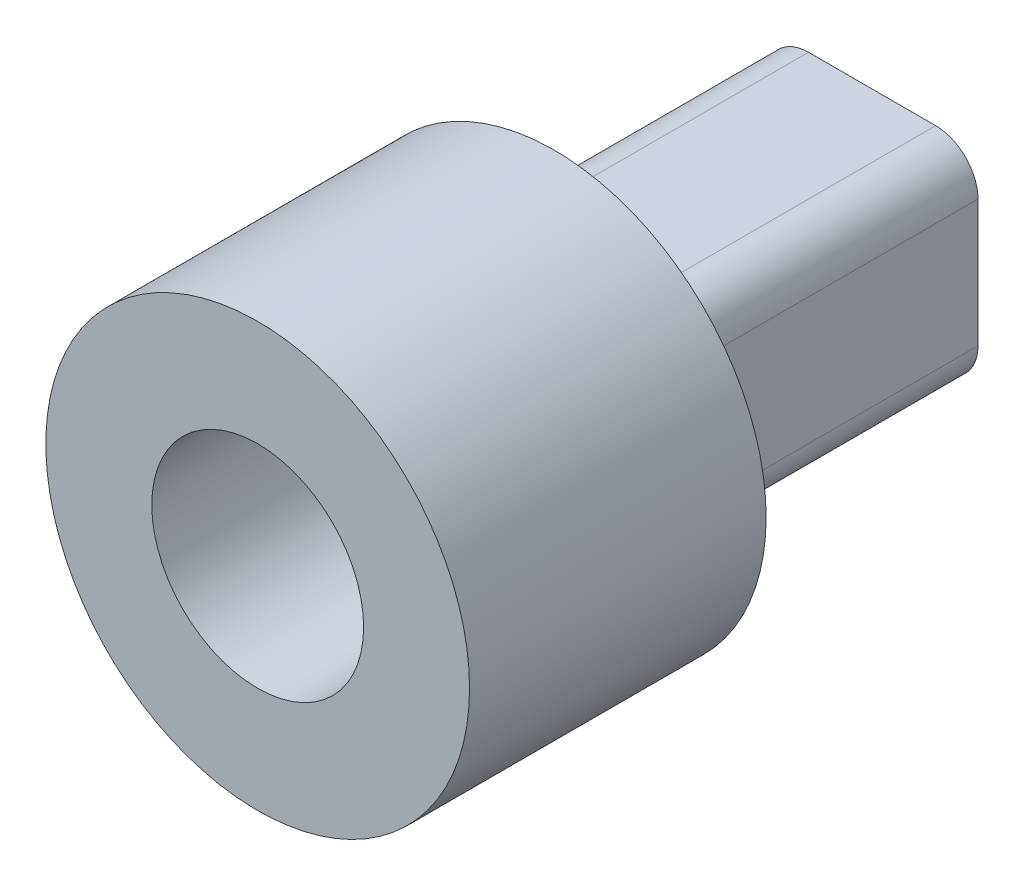
SolidWorks part; units mm, degrees
ref_plane "Front Plane" through (0, 0, 0) normal (0, 0, 1) x (1, 0, 0)
ref_plane "Top Plane" through (0, 0, 0) normal (0, 1, 0) x (1, 0, 0)
ref_plane "Right Plane" through (0, 0, 0) normal (1, 0, 0) x (0, 0, -1)
sketch "Sketch1" plane through (0, 0, 0) normal (0, 0, 1) x (1, 0, 0)
  line L1 (-1.5, -2.5) -> (1.5, -2.5)
  line L2 (-2.5, -1.5) -> (-2.5, 1.5)
  line L3 (-1.5, 2.5) -> (1.5, 2.5)
  line L4 (2.5, -1.5) -> (2.5, 1.5)
  line L5 (-2.5, -2.5) -> (2.5, 2.5) construction
  line L6 (-2.5, 2.5) -> (2.5, -2.5) construction
  arc A0 (1.5, 2.5) -> (2.5, 1.5) centre (1.5, 1.5) cw
  arc A1 (1.5, -2.5) -> (2.5, -1.5) centre (1.5, -1.5) ccw
  arc A2 (-1.5, -2.5) -> (-2.5, -1.5) centre (-1.5, -1.5) cw
  arc A3 (-2.5, 1.5) -> (-1.5, 2.5) centre (-1.5, 1.5) cw
  point P0 (0, 0)
  dimension "D3" = 1
  dimension "D1" = 5
  dimension "D2" = 5
extrude "Boss-Extrude1" add sketch "Sketch1" along normal blind 7.5
sketch "Sketch2" plane through (0, 0, 7.5) normal (0, 0, 1) x (1, 0, 0)
  circle A0 centre (0, 0) radius 5
  dimension "D1" = 10
extrude "Boss-Extrude2" add sketch "Sketch2" along normal blind 2
sketch "Sketch3" plane through (0, 0, 9.5) normal (0, 0, 1) x (1, 0, 0)
  circle A0 centre (0, 0) radius 2.5
  circle A1 centre (0, 0) radius 5
  circle M2 centre (0, 0) radius 5
  dimension "D1" = 5
  dimension "D2" = 10
extrude "Boss-Extrude3" add sketch "Sketch3" along normal blind 5 contours A0 M2 | A1
fillet "Fillet1" radius 1 8 edges at (0, 2.5, 7.5) (2.2071, 2.2071, 7.5) (2.5, 0, 7.5) (2.2071, -2.2071, 7.5) (0, -2.5, 7.5) (-2.2071, -2.2071, 7.5) (-2.5, 0, 7.5) (-2.2071, 2.2071, 7.5)
